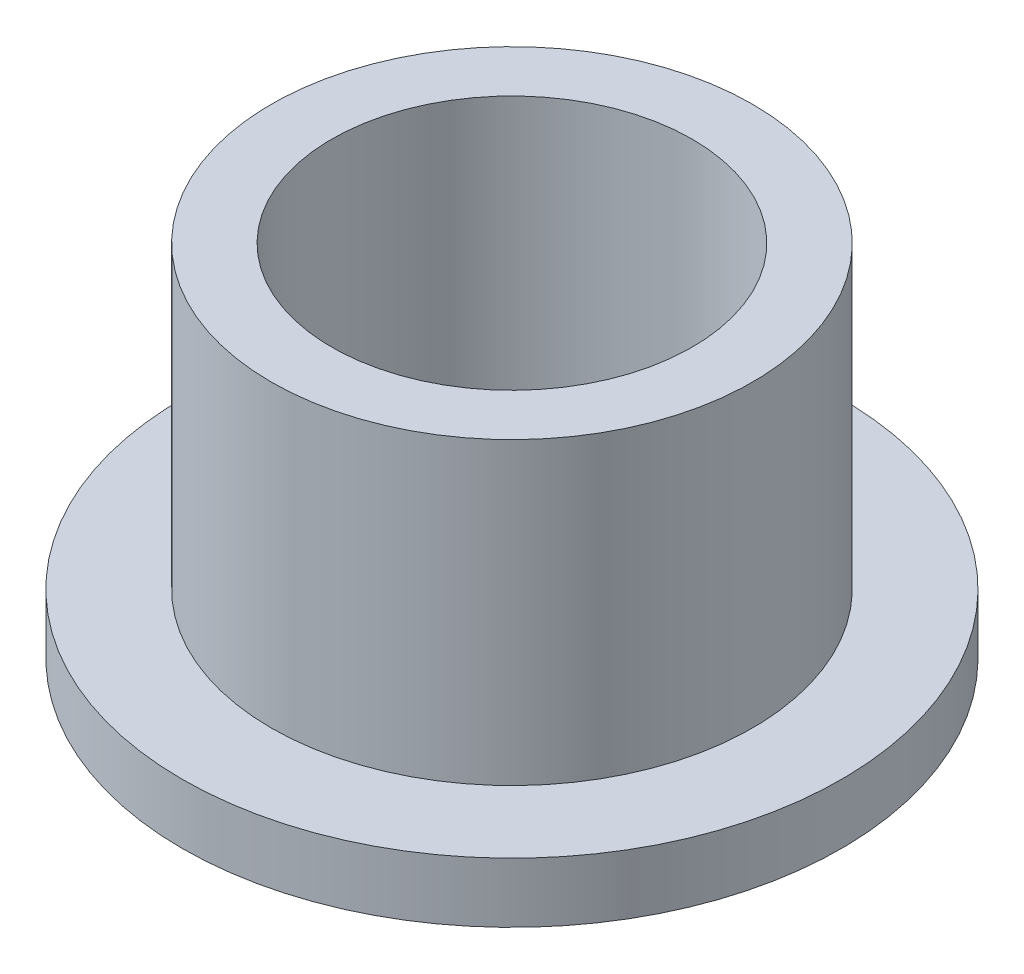
SolidWorks part; units mm, degrees
material "Tin Bearing Bronze"
ref_plane "Front" through (0, 0, 0) normal (0, 0, 1) x (1, 0, 0)
ref_plane "Top" through (0, 0, 0) normal (0, 1, 0) x (1, 0, 0)
ref_plane "Right" through (0, 0, 0) normal (1, 0, 0) x (0, 0, -1)
sketch "Sketch1" plane through (0, 0, 0) normal (0, 1, 0) x (1, 0, 0)
  circle A0 centre (0, 0) radius 4.7752
  circle A1 centre (0, 0) radius 6.3754
  circle A2 centre (0, 0) radius 8.7312
  dimension "ID" = 9.5504
  dimension "OD" = 12.7508
  dimension "FlangeOD" = 17.4625
sketch "Sketch2" plane through (0, 0, 0) normal (0, 1, 0) x (1, 0, 0)
  circle A0 centre (0, 0) radius 4.7752 construction
  circle A1 centre (0, 0) radius 6.3754 construction
  circle A2 centre (0, 0) radius 4.7752
  circle A3 centre (0, 0) radius 6.3754
extrude "Boss-Extrude1" add sketch "Sketch2" along normal blind 9.525
sketch "Sketch3" plane through (0, 0, 0) normal (0, 1, 0) x (1, 0, 0)
  circle A0 centre (0, 0) radius 8.7312 construction
  circle A1 centre (0, 0) radius 6.3754 construction
  circle A2 centre (0, 0) radius 8.7312
  circle A3 centre (0, 0) radius 6.3754
extrude "Boss-Extrude2" add sketch "Sketch3" along normal blind 1.5875
